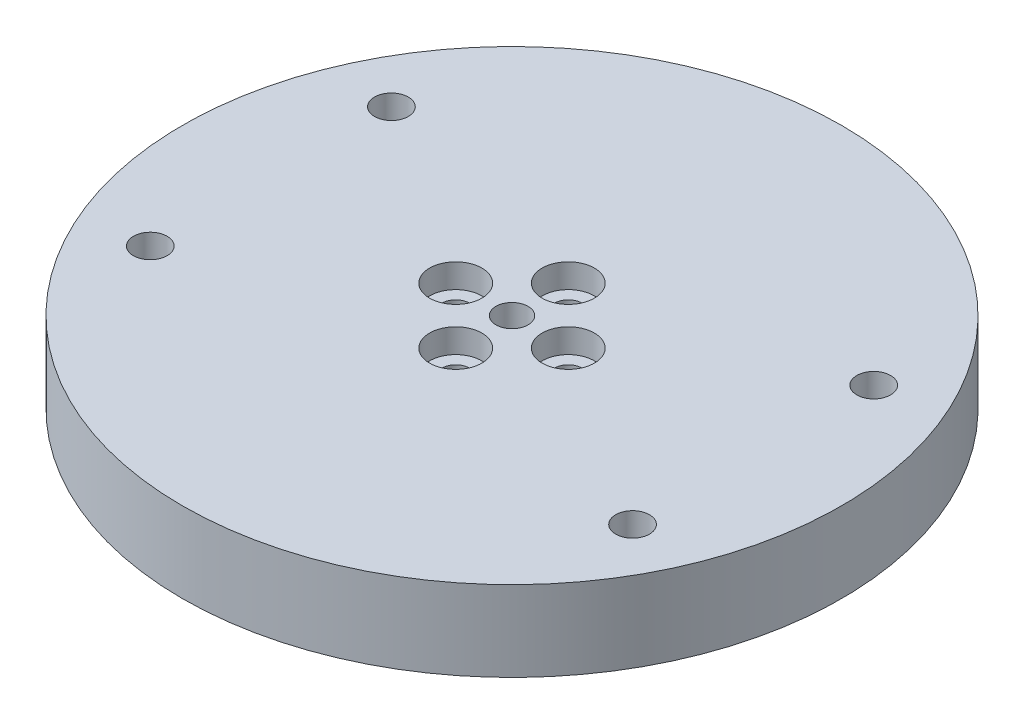
SolidWorks part; units mm, degrees
ref_plane "Front Plane" through (0, 0, 0) normal (0, 0, 1) x (1, 0, 0)
ref_plane "Top Plane" through (0, 0, 0) normal (0, 1, 0) x (1, 0, 0)
ref_plane "Right Plane" through (0, 0, 0) normal (1, 0, 0) x (0, 0, -1)
sketch "Sketch1" plane through (0, 0, 0) normal (0, 1, 0) x (1, 0, 0)
  circle A0 centre (0, 0) radius 41
extrude "Boss-Extrude1" add sketch "Sketch1" along normal blind 10
sketch "Sketch2" plane through (0, 0, 0) normal (0, -1, 0) x (1, 0, 0)
  circle A0 centre (0, 0) radius 10.1
extrude "Cut-Extrude1" cut sketch "Sketch2" against normal blind 0.5
sketch "Sketch3" plane through (0, 0.5, 0) normal (0, -1, 0) x (1, 0, 0)
  circle A1 centre (0, 7) radius 1.7
  circle A2 centre (7, 0) radius 1.7
  circle A3 centre (0, -7) radius 1.7
  circle A4 centre (-7, 0) radius 1.7
  circle A5 centre (0, 0) radius 2
  point P14 (0, 0)
  dimension "D1" = 4
extrude "Cut-Extrude2" cut sketch "Sketch3" against normal through all
sketch "Sketch4" plane through (0, 10, 0) normal (0, 1, 0) x (1, 0, 0)
  circle A0 centre (0, 7) radius 3.25
  circle A1 centre (7, 0) radius 3.25
  circle A2 centre (0, -7) radius 3.25
  circle A3 centre (-7, 0) radius 3.25
  point P12 (0, 0)
  dimension "D1" = 4
extrude "Cut-Extrude3" cut sketch "Sketch4" against normal blind 3
sketch "Sketch5" plane through (0, 10, 0) normal (0, 1, 0) x (1, 0, 0)
  line L5 (-30, 15) -> (30, -15) construction
  line L6 (-30, -15) -> (30, 15) construction
  circle A0 centre (-30, 15) radius 2.1
  circle A1 centre (-30, -15) radius 2.1
  circle A2 centre (30, 15) radius 2.1
  circle A3 centre (30, -15) radius 2.1
  point P0 (0, 0)
  dimension "D1" = 30
  dimension "D2" = 60
extrude "Cut-Extrude4" cut sketch "Sketch5" against normal blind 5.5
